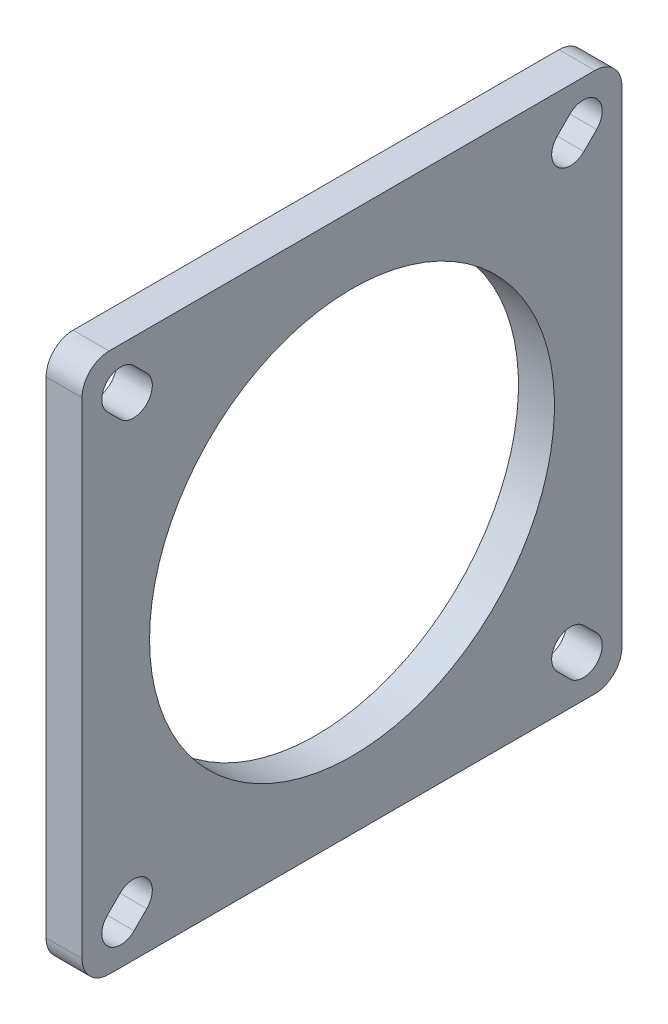
SolidWorks part; units mm, degrees
material "1060 Сплав"
ref_plane "Спереди" through (0, 0, 0) normal (0, 0, 1) x (1, 0, 0)
ref_plane "Сверху" through (0, 0, 0) normal (0, 1, 0) x (1, 0, 0)
ref_plane "Справа" through (0, 0, 0) normal (1, 0, 0) x (0, 0, -1)
sketch "Эскиз1" plane through (0, 0, 0) normal (0, 0, 1) x (1, 0, 0)
  line L0 (0, 22.5) -> (0, 50)
  line L1 (0, 50) -> (4, 50)
  line L2 (4, 50) -> (4, 22.5)
  line L3 (4, 22.5) -> (0, 22.5)
  line L4 (-29.3651, 0) -> (90.6978, 0) construction
  dimension "D1" = 45
  dimension "D2" = 100
  dimension "D3" = 4
revolve "Повернуть1" add sketch "Эскиз1" angle 360 about L4
sketch "Эскиз7" plane through (0, 0, 0) normal (-1, 0, 0) x (0, 0, 1)
  line L1 (30, -30) -> (-30, -30)
  line L2 (30, -30) -> (30, 30)
  line L3 (30, 30) -> (-30, 30)
  line L4 (-30, -30) -> (-30, 30)
  circle A0 centre (0, 0) radius 50 construction
  circle A1 centre (0, 0) radius 50
  point P0 (0, 0)
  dimension "D1" = 60
  dimension "D2" = 60
  dimension "D3" = 30
  dimension "D4" = 30
extrude "Вырез-Вытянуть4" cut sketch "Эскиз7" against normal through all both and the other way through all
sketch "Эскиз6" plane through (0, 0, 0) normal (-1, 0, 0) x (0, 0, 1)
  line L0 (-27.192, 24.2222) -> (-25.7778, 22.808)
  line L1 (-24.2222, 27.192) -> (-22.808, 25.7778)
  line L2 (0, 0) -> (0, 50000) construction
  line L4 (-26.4849, 23.5151) -> (-23.5151, 26.4849) construction
  line L5 (-15.9099, 15.9099) -> (35339.4292, -35339.4292) construction
  arc A0 (-24.2222, 27.192) -> (-27.192, 24.2222) centre (-25.7071, 25.7071) ccw
  arc A1 (-25.7778, 22.808) -> (-22.808, 25.7778) centre (-24.2929, 24.2929) ccw
  circle A2 centre (0, 0) radius 35.3553 construction
  point P11 (-25, 25)
  dimension "D1" = 2
  dimension "D3" = 25
  dimension "D2" = 4.2
  dimension "D4" = 45
extrude "Вырез-Вытянуть3" cut sketch "Эскиз6" against normal through all both and the other way through all
pattern_circular "Круговой массив2" count 4 over 360 about axis through (0, 0, 0) along (1, 0, 0) of "Вырез-Вытянуть3"
fillet "Скругление1" radius 3 4 edges at (2, -30, -30) (2, -30, 30) (2, 30, 30) (2, 30, -30)
